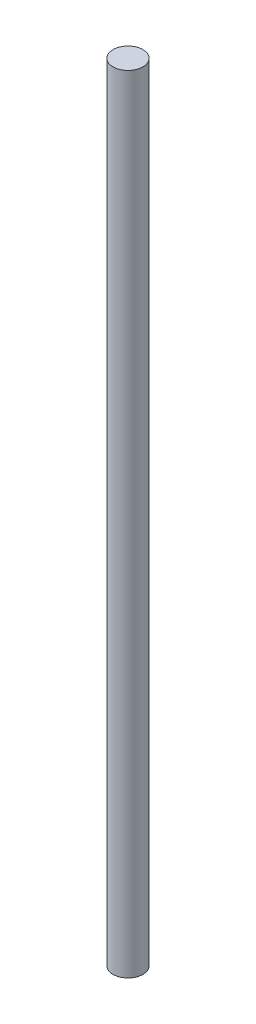
SolidWorks part; units mm, degrees
ref_plane "Front Plane" through (0, 0, 0) normal (0, 0, 1) x (1, 0, 0)
ref_plane "Top Plane" through (0, 0, 0) normal (0, 1, 0) x (1, 0, 0)
ref_plane "Right Plane" through (0, 0, 0) normal (1, 0, 0) x (0, 0, -1)
sketch "Sketch1" plane through (0, 0, 0) normal (0, 1, 0) x (1, 0, 0)
  circle A0 centre (0, 0) radius 4
  dimension "D1" = 8
extrude "Boss-Extrude1" add sketch "Sketch1" along normal blind 210
